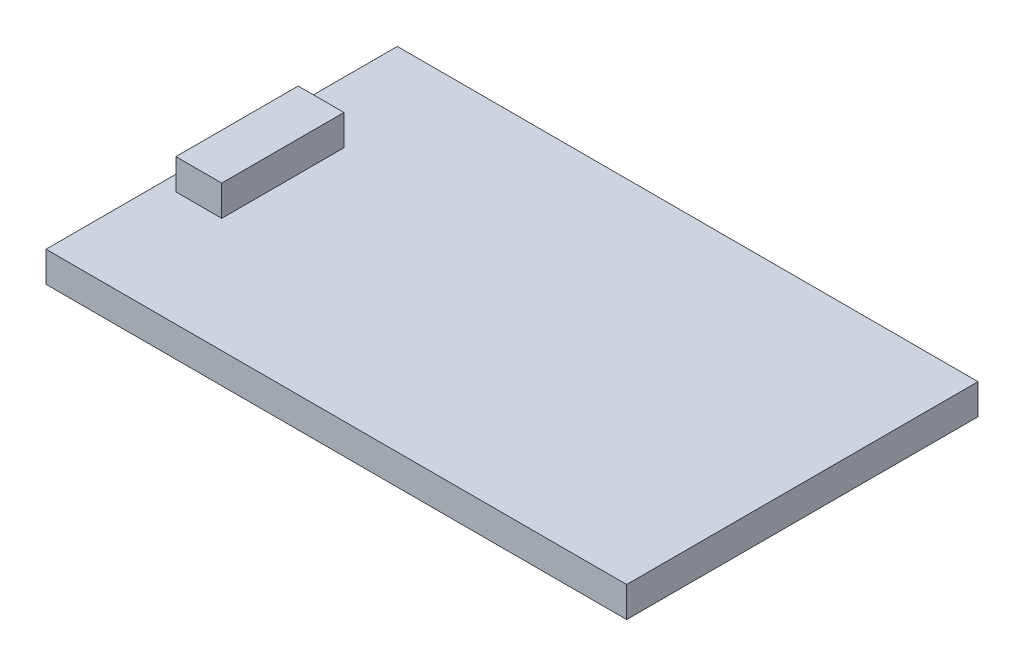
SolidWorks part; units mm, degrees
ref_plane "Front Plane" through (0, 0, 0) normal (0, 0, 1) x (1, 0, 0)
ref_plane "Top Plane" through (0, 0, 0) normal (0, 1, 0) x (1, 0, 0)
ref_plane "Right Plane" through (0, 0, 0) normal (1, 0, 0) x (0, 0, -1)
sketch "Sketch1" plane through (0, 0, 0) normal (0, 1, 0) x (1, 0, 0)
  line L1 (-19, -11.495) -> (19, -11.495)
  line L2 (-19, -11.495) -> (-19, 11.495)
  line L3 (-19, 11.495) -> (19, 11.495)
  line L4 (19, -11.495) -> (19, 11.495)
  line L5 (-19, -11.495) -> (19, 11.495) construction
  line L6 (-19, 11.495) -> (19, -11.495) construction
  point P0 (0, 0)
  dimension "D1" = 38
  dimension "D2" = 22.99
extrude "Boss-Extrude1" add sketch "Sketch1" along normal blind 1.99
sketch "Sketch2" plane through (0, 1.99, 0) normal (0, 1, 0) x (1, 0, 0)
  line L0 (-19, 11.495) -> (-19, -11.495) construction
  line L1 (-18, 4.005) -> (-15, 4.005)
  line L2 (-18, 4.005) -> (-18, -3.995)
  line L3 (-18, -3.995) -> (-15, -3.995)
  line L4 (-15, 4.005) -> (-15, -3.995)
  line L6 (19, 11.495) -> (-19, 11.495) construction
  point P4 (-18, 0.005)
  dimension "D1" = 3
  dimension "D2" = 8
  dimension "D3" = 1
  dimension "D4" = 7.49
extrude "Boss-Extrude2" add sketch "Sketch2" along normal blind 2
equation "\"fit width\"= 23mm"
equation "\"nominal thickness\"= 2mm"
equation "\"lid length\"= 38mm"
equation "\"lid thickness\"= \"nominal thickness\" - 0.00508mm"
equation "\"lid width\"= \"fit width\" - 0.0127mm"
